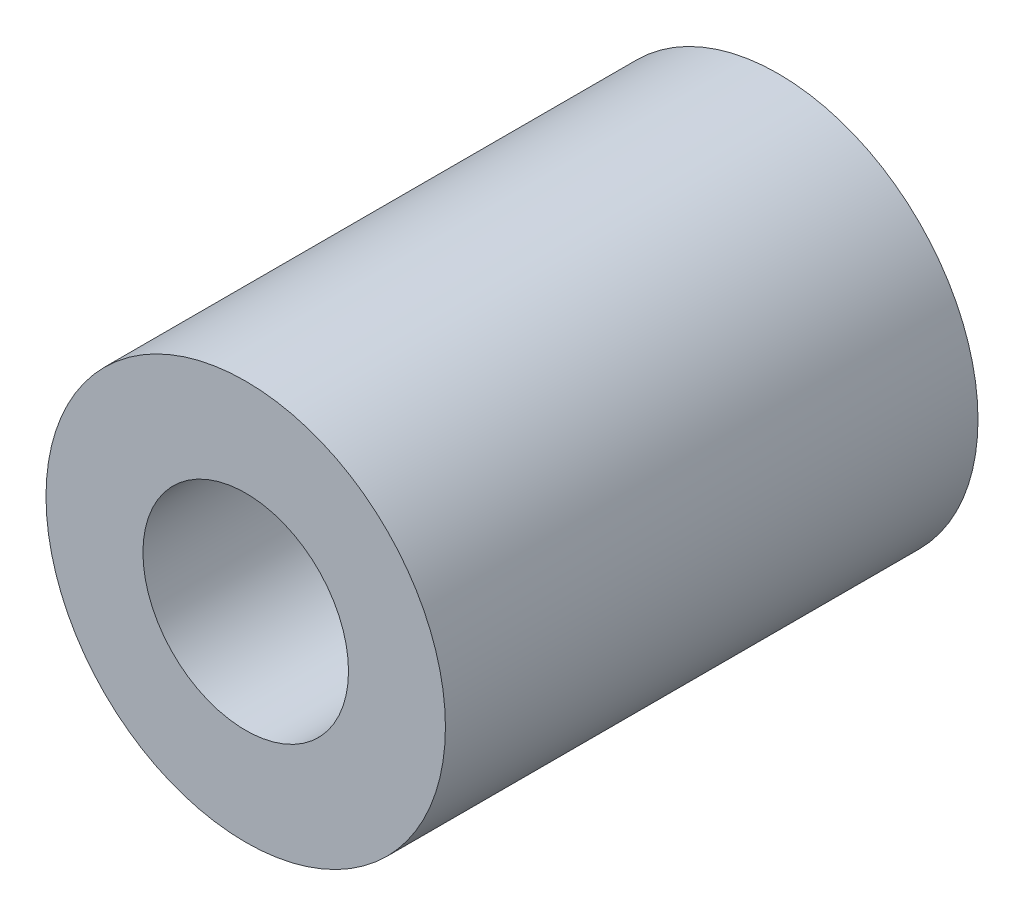
SolidWorks part; units mm, degrees
ref_plane "Front Plane" through (0, 0, 0) normal (0, 0, 1) x (1, 0, 0)
ref_plane "Top Plane" through (0, 0, 0) normal (0, 1, 0) x (1, 0, 0)
ref_plane "Right Plane" through (0, 0, 0) normal (1, 0, 0) x (0, 0, -1)
sketch "Sketch1" plane through (0, 0, 0) normal (0, 0, 1) x (1, 0, 0)
  circle A0 centre (0, 0) radius 2.4511
  circle A1 centre (0, 0) radius 4.7625
extrude "Boss-Extrude1" add sketch "Sketch1" along normal blind 12.7
